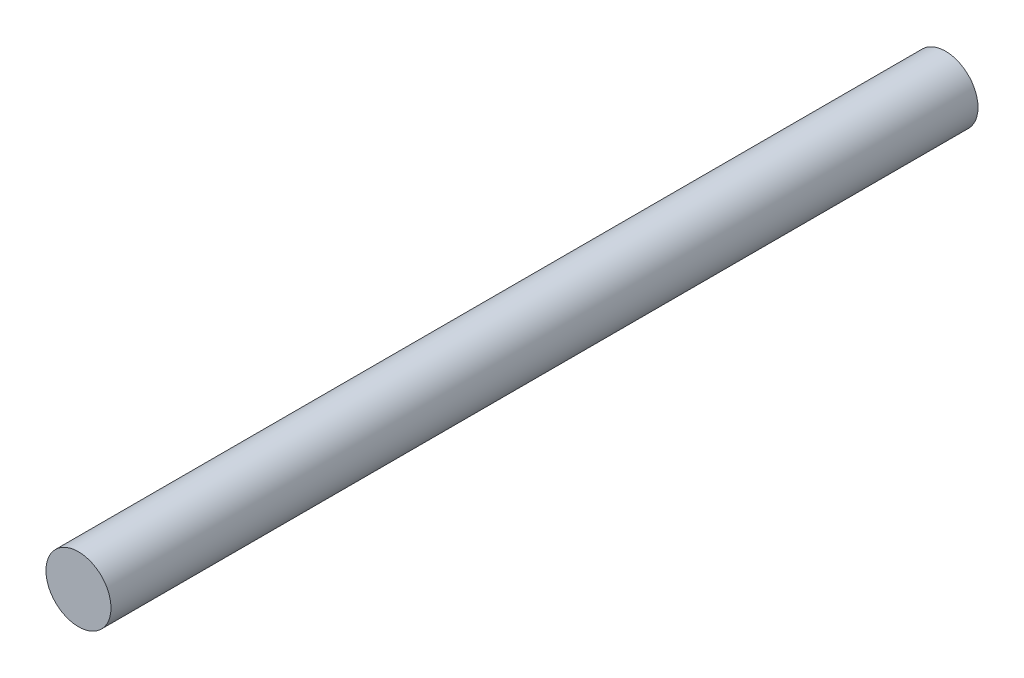
SolidWorks part; units mm, degrees
material "Alloy Steel"
ref_plane "Front Plane" through (0, 0, 0) normal (0, 0, 1) x (1, 0, 0)
ref_plane "Top Plane" through (0, 0, 0) normal (0, 1, 0) x (1, 0, 0)
ref_plane "Right Plane" through (0, 0, 0) normal (1, 0, 0) x (0, 0, -1)
sketch "Sketch1" plane through (0, 0, 0) normal (0, 0, 1) x (1, 0, 0)
  circle A0 centre (0, 0) radius 1.5
  dimension "D1" = 3
extrude "Sprint Boss-Extrude1" add sketch "Sketch1" along normal blind 40
